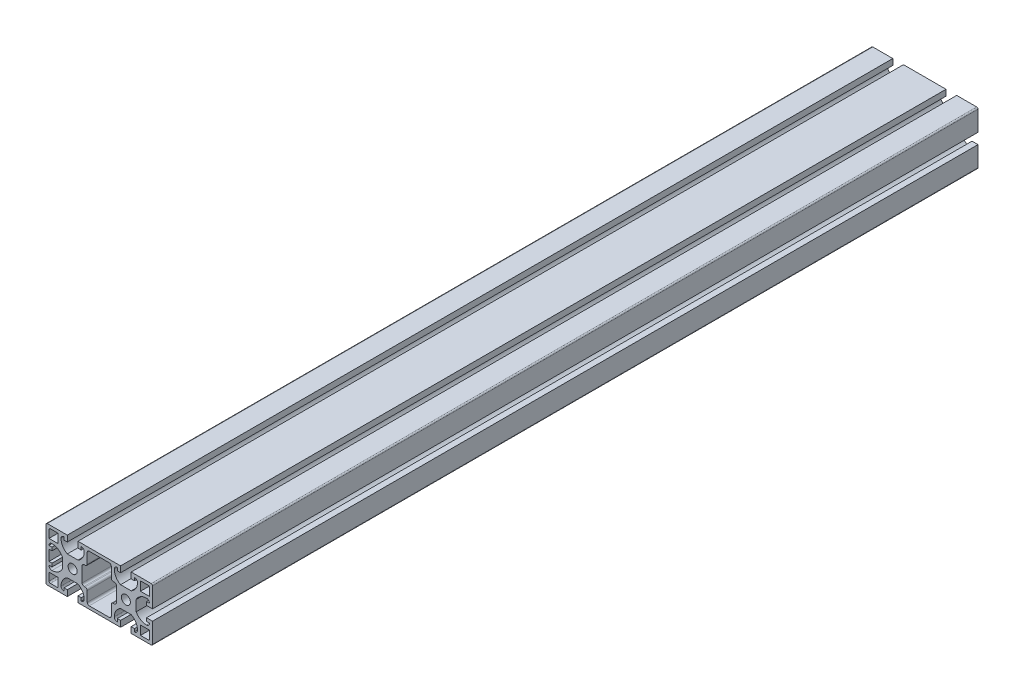
SolidWorks part; units mm, degrees
material "3.0255 (EN-AW 1350A)"
ref_plane "Płaszczyzna przednia" through (0, 0, 0) normal (0, 0, 1) x (1, 0, 0)
ref_plane "Płaszczyzna górna" through (0, 0, 0) normal (0, 1, 0) x (1, 0, 0)
ref_plane "Płaszczyzna prawa" through (0, 0, 0) normal (1, 0, 0) x (0, 0, -1)
sketch "Szkic1" plane through (0, 0, 0) normal (0, 0, 1) x (1, 0, 0)
  line L0 (0, 20) -> (0, -20) construction
  line L1 (-51.8865, 0) -> (40, 0) construction
  line L4 (-40, -19) -> (-40, 19)
  line L7 (-40, -20) -> (0, 0) construction
  line L8 (-40, 20) -> (40, -20) construction
  line L13 (20, 20) -> (20, 0) construction
  line L15 (24, 20) -> (24, 15.5)
  line L16 (24, 15.5) -> (26.4714, 15.5)
  line L21 (16, 15.5) -> (13.5286, 15.5)
  line L23 (16, 20) -> (13.5286, 20)
  line L24 (16, 20) -> (16, 15.5)
  line L25 (16, 7.75) -> (24, 7.75)
  line L26 (13.5286, 15.5) -> (13.5286, 17.75)
  line L27 (26.4714, 15.5) -> (26.4714, 17.75)
  line L28 (-24, 20) -> (-24, 15.5)
  line L29 (-26.4714, 15.5) -> (-26.4714, 17.75)
  line L30 (-24, 15.5) -> (-26.4714, 15.5)
  line L31 (-13.5286, 15.5) -> (-13.5286, 17.75)
  line L32 (-16, 15.5) -> (-13.5286, 15.5)
  line L33 (-16, 20) -> (-16, 15.5)
  line L34 (-16, 7.75) -> (-24, 7.75)
  line L35 (20, -20) -> (20, 0) construction
  line L36 (-40, -20) -> (0, 0) construction
  line L37 (-40, 20) -> (40, -20) construction
  line L38 (30.9714, -17.75) -> (36.75, -17.75)
  line L39 (-16, -7.75) -> (-24, -7.75)
  line L40 (-16, -20) -> (-16, -15.5)
  line L41 (-16, -15.5) -> (-13.5286, -15.5)
  line L42 (-13.5286, -15.5) -> (-13.5286, -17.75)
  line L43 (-24, -15.5) -> (-26.4714, -15.5)
  line L44 (-26.4714, -15.5) -> (-26.4714, -17.75)
  line L45 (-24, -20) -> (-24, -15.5)
  line L46 (26.4714, -15.5) -> (26.4714, -17.75)
  line L47 (13.5286, -15.5) -> (13.5286, -17.75)
  line L48 (16, -7.75) -> (24, -7.75)
  line L49 (16, -20) -> (16, -15.5)
  line L50 (16, -15.5) -> (13.5286, -15.5)
  line L51 (24, -15.5) -> (26.4714, -15.5)
  line L52 (24, -20) -> (24, -15.5)
  line L53 (40, -20) -> (0, 20) construction
  line L54 (35.5, 6.4714) -> (37.75, 6.4714)
  line L55 (35.5, 4) -> (35.5, 6.4714)
  line L56 (40, 4) -> (35.5, 4)
  line L57 (40, -4) -> (35.5, -4)
  line L58 (35.5, -4) -> (35.5, -6.4714)
  line L59 (35.5, -6.4714) -> (37.75, -6.4714)
  line L60 (27.75, 4) -> (27.75, -4)
  line L61 (-35.5, -6.4714) -> (-37.75, -6.4714)
  line L62 (-37.75, -4) -> (-35.5, -4)
  line L63 (-35.5, -4) -> (-35.5, -6.4714)
  line L64 (-35.5, 4) -> (-35.5, 6.4714)
  line L65 (-35.5, 6.4714) -> (-37.75, 6.4714)
  line L66 (-37.75, 4) -> (-35.5, 4)
  line L67 (-27.75, 4) -> (-27.75, -4)
  line L68 (-37.75, 4) -> (-37.75, -4)
  line L69 (40, -4) -> (40, -19)
  line L70 (40, 19) -> (40, 4)
  line L71 (-39, -20) -> (-24, -20)
  line L72 (-16, -20) -> (16, -20)
  line L73 (24, -20) -> (39, -20)
  line L74 (13.5286, 20) -> (-16, 20)
  line L75 (-24, 20) -> (-39, 20)
  line L76 (24, 20) -> (39, 20)
  line L77 (10.5286, 7.0902) -> (11.4095, 7.0902)
  line L78 (-7.5286, -17.75) -> (7.5286, -17.75)
  line L79 (-9.0286, -16.25) -> (-9.0286, -8.5902)
  line L80 (-7.5286, 17.75) -> (7.5286, 17.75)
  line L81 (9.0286, -16.25) -> (9.0286, -8.5902)
  line L82 (-9.0286, -17.75) -> (9.0286, 17.75) construction
  line L83 (-9.0286, 17.75) -> (9.0286, -17.75) construction
  line L84 (-11.4095, -7.0902) -> (-10.5286, -7.0902)
  line L85 (-12.9095, -5.5902) -> (-12.9095, 5.5902)
  line L86 (-11.4095, 7.0902) -> (-10.5286, 7.0902)
  line L87 (12.9095, -5.5902) -> (12.9095, 5.5902)
  line L88 (-12.9095, -7.0902) -> (0, 0) construction
  line L89 (-12.9095, 7.0902) -> (12.9095, -7.0902) construction
  line L90 (-9.0286, 8.5902) -> (-9.0286, 16.25)
  line L91 (-9.0286, 4.5143) -> (-9.0286, 4.9587)
  line L92 (-9.0286, -4.9587) -> (-9.0286, -4.5143)
  line L93 (9.0286, 8.5902) -> (9.0286, 16.25)
  line L94 (10.5286, -7.0902) -> (11.4095, -7.0902)
  line L96 (0, 0) -> (12.9095, 7.0902) construction
  line L98 (37.75, -10.9714) -> (37.75, -16.75)
  line L99 (30.9714, 10.9714) -> (37.75, 10.9714)
  line L100 (30.9714, 10.9714) -> (30.9714, 17.75)
  line L101 (30.9714, 17.75) -> (36.75, 17.75)
  line L102 (37.75, 10.9714) -> (37.75, 16.75)
  line L103 (30.9714, 10.9714) -> (37.75, 17.75) construction
  line L104 (30.9714, 17.75) -> (37.75, 10.9714) construction
  line L105 (30.9714, -10.9714) -> (37.75, -10.9714)
  line L106 (30.9714, -10.9714) -> (30.9714, -17.75)
  line L107 (-30.9714, -10.9714) -> (-30.9714, -17.75)
  line L108 (-30.9714, -10.9714) -> (-37.75, -10.9714)
  line L109 (-37.75, -10.9714) -> (-37.75, -16.75)
  line L110 (-30.9714, -17.75) -> (-36.75, -17.75)
  line L111 (-30.9714, 17.75) -> (-36.75, 17.75)
  line L112 (-37.75, 10.9714) -> (-37.75, 16.75)
  line L113 (-30.9714, 10.9714) -> (-37.75, 10.9714)
  line L114 (-30.9714, 10.9714) -> (-30.9714, 17.75)
  circle A0 centre (-20, 0) radius 3.4
  circle A1 centre (20, 0) radius 3.4
  arc A2 (26.4714, 17.75) -> (28.7214, 15.5) centre (26.4714, 15.5) cw
  arc A3 (28.7214, 15.5) -> (24, 7.75) centre (20, 15.5) cw
  arc A4 (13.5286, 17.75) -> (11.2786, 15.5) centre (13.5286, 15.5) ccw
  arc A5 (11.2786, 15.5) -> (16, 7.75) centre (20, 15.5) ccw
  arc A6 (-26.4714, 17.75) -> (-28.7214, 15.5) centre (-26.4714, 15.5) ccw
  arc A7 (-13.5286, 17.75) -> (-11.2786, 15.5) centre (-13.5286, 15.5) cw
  arc A8 (-11.2786, 15.5) -> (-16, 7.75) centre (-20, 15.5) cw
  arc A9 (-28.7214, 15.5) -> (-24, 7.75) centre (-20, 15.5) ccw
  arc A10 (-28.7214, -15.5) -> (-24, -7.75) centre (-20, -15.5) cw
  arc A11 (-11.2786, -15.5) -> (-16, -7.75) centre (-20, -15.5) ccw
  arc A12 (-13.5286, -17.75) -> (-11.2786, -15.5) centre (-13.5286, -15.5) ccw
  arc A13 (-26.4714, -17.75) -> (-28.7214, -15.5) centre (-26.4714, -15.5) cw
  arc A14 (11.2786, -15.5) -> (16, -7.75) centre (20, -15.5) cw
  arc A15 (13.5286, -17.75) -> (11.2786, -15.5) centre (13.5286, -15.5) cw
  arc A16 (28.7214, -15.5) -> (24, -7.75) centre (20, -15.5) ccw
  arc A17 (26.4714, -17.75) -> (28.7214, -15.5) centre (26.4714, -15.5) ccw
  arc A18 (35.5, 8.7214) -> (27.75, 4) centre (35.5, 0) ccw
  arc A19 (37.75, 6.4714) -> (35.5, 8.7214) centre (35.5, 6.4714) ccw
  arc A20 (37.75, -6.4714) -> (35.5, -8.7214) centre (35.5, -6.4714) cw
  arc A21 (35.5, -8.7214) -> (27.75, -4) centre (35.5, 0) cw
  arc A22 (-35.5, -8.7214) -> (-27.75, -4) centre (-35.5, 0) ccw
  arc A23 (-37.75, -6.4714) -> (-35.5, -8.7214) centre (-35.5, -6.4714) ccw
  arc A24 (-37.75, 6.4714) -> (-35.5, 8.7214) centre (-35.5, 6.4714) cw
  arc A25 (-35.5, 8.7214) -> (-27.75, 4) centre (-35.5, 0) cw
  arc A26 (-10.5286, 7.0902) -> (-9.0286, 8.5902) centre (-10.5286, 8.5902) ccw
  arc A27 (-9.0286, -8.5902) -> (-10.5286, -7.0902) centre (-10.5286, -8.5902) ccw
  arc A28 (11.4095, -7.0902) -> (12.9095, -5.5902) centre (11.4095, -5.5902) ccw
  arc A29 (9.0286, -8.5902) -> (10.5286, -7.0902) centre (10.5286, -8.5902) cw
  arc A30 (7.5286, -17.75) -> (9.0286, -16.25) centre (7.5286, -16.25) ccw
  arc A31 (-7.5286, -17.75) -> (-9.0286, -16.25) centre (-7.5286, -16.25) cw
  arc A32 (-11.4095, -7.0902) -> (-12.9095, -5.5902) centre (-11.4095, -5.5902) cw
  arc A33 (-12.9095, 5.5902) -> (-11.4095, 7.0902) centre (-11.4095, 5.5902) cw
  arc A34 (-9.0286, 16.25) -> (-7.5286, 17.75) centre (-7.5286, 16.25) cw
  arc A35 (7.5286, 17.75) -> (9.0286, 16.25) centre (7.5286, 16.25) cw
  arc A36 (11.4095, 7.0902) -> (12.9095, 5.5902) centre (11.4095, 5.5902) cw
  arc A37 (10.5286, 7.0902) -> (9.0286, 8.5902) centre (10.5286, 8.5902) cw
  arc A38 (-40, 19) -> (-39, 20) centre (-39, 19) cw
  arc A39 (-39, -20) -> (-40, -19) centre (-39, -19) cw
  arc A40 (39, -20) -> (40, -19) centre (39, -19) ccw
  arc A41 (39, 20) -> (40, 19) centre (39, 19) cw
  arc A42 (36.75, 17.75) -> (37.75, 16.75) centre (36.75, 16.75) cw
  arc A43 (36.75, -17.75) -> (37.75, -16.75) centre (36.75, -16.75) ccw
  arc A44 (-36.75, -17.75) -> (-37.75, -16.75) centre (-36.75, -16.75) cw
  arc A45 (-36.75, 17.75) -> (-37.75, 16.75) centre (-36.75, 16.75) ccw
  point P5 (0, 0)
  point P17 (0, 0)
  point P30 (24, 17.75)
  point P108 (0, 0)
  point P124 (-9.0286, 7.0902)
  point P132 (9.0286, -7.0902)
  point P156 (9.0286, 7.0902)
  point P161 (40, 20)
  point P162 (34.3607, 14.3607)
  dimension "D4" = 6.8
  dimension "D5" = 12.25
  dimension "D9" = 11
  dimension "D11" = 1.5
  dimension "D12" = 1
  dimension "D16" = 1
  dimension "D1" = 80
  dimension "D2" = 40
  dimension "D3" = 40
  dimension "D6" = 2.25
  dimension "D7" = 8
  dimension "D8" = 4.5
  dimension "D10" = 14.1804
  dimension "D13" = 2.25
  dimension "D14" = 2.25
  dimension "D15" = 2.25
extrude "Dodanie-wyciągnięcie1" add sketch "Szkic1" along normal blind 620 contours A20 A21 L60 A18 A19 L54 L55 L56 L70 L76 L15 L16 L27 A2 A3 L25 A5 A4 L26 L21 L24 L23 L74 L33 L32 L31 A7 A8 L34 A9 A6 L29 L30 L28 L75 L4 L71 L45 L43 L44 A13 A10 L39 A11 A12 L42 L41 L40 L72 L49 L50
